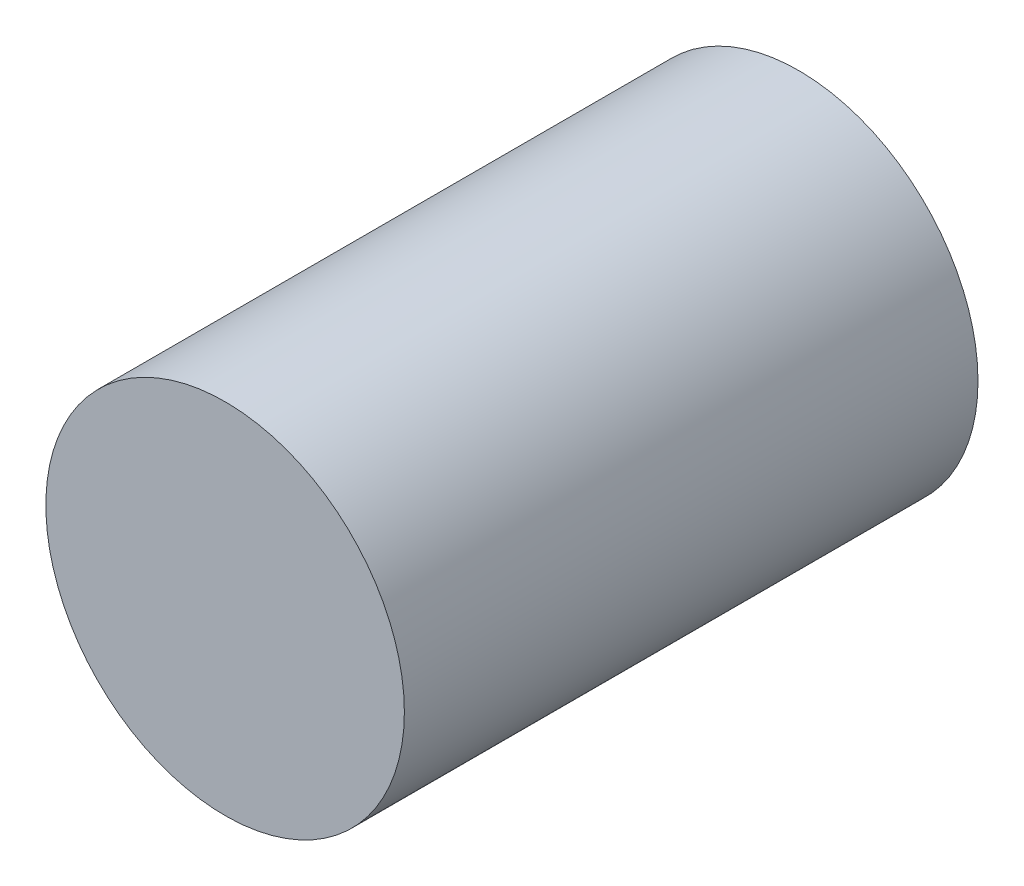
SolidWorks part; units mm, degrees
ref_plane "Front Plane" through (0, 0, 0) normal (0, 0, 1) x (1, 0, 0)
ref_plane "Top Plane" through (0, 0, 0) normal (0, 1, 0) x (1, 0, 0)
ref_plane "Right Plane" through (0, 0, 0) normal (1, 0, 0) x (0, 0, -1)
sketch "Sketch1" plane through (0, 0, 0) normal (0, 0, 1) x (1, 0, 0)
  circle A0 centre (0, 0) radius 5
  dimension "D1" = 10
extrude "Boss-Extrude1" add sketch "Sketch1" along normal blind 16
